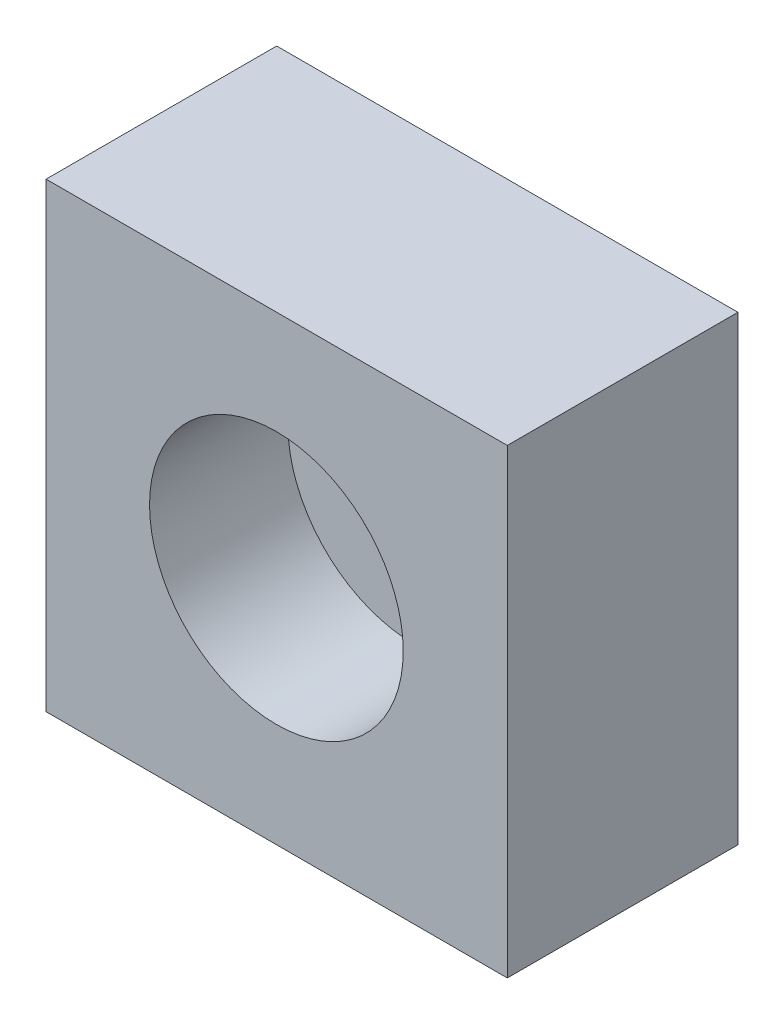
SolidWorks part; units mm, degrees
ref_plane "前视基准面" through (0, 0, 0) normal (0, 0, 1) x (1, 0, 0)
ref_plane "上视基准面" through (0, 0, 0) normal (0, 1, 0) x (1, 0, 0)
ref_plane "右视基准面" through (0, 0, 0) normal (1, 0, 0) x (0, 0, -1)
other "Configuration Table"
sketch "草图1" plane through (0, 0, 0) normal (0, 0, 1) x (1, 0, 0)
  line L1 (0, 0) -> (20, 0)
  line L2 (0, 0) -> (0, 20)
  line L3 (0, 20) -> (20, 20)
  line L4 (20, 0) -> (20, 20)
extrude "BaseBox" add sketch "草图1" along normal blind 10
hole_wizard "Hole_cb_ansi_metric_socket_m6" positions "草图3" profile "草图2" counterbore size "M6" standard "ANSI Metric" end condition through all
sketch "草图3" plane through (0, 0, 10) normal (0, 0, 1) x (1, 0, 0)
  point P0 (9.9865, 10.0143)
sketch "草图2" plane through (9.9865, 10.0143, 10) normal (1, 0, 0) x (0, -1, 0)
  line L0 (0, 0) -> (0, 10)
  line L1 (0, 10) -> (3, 10)
  line L3 (3, 10) -> (3, 6)
  line L4 (3, 6) -> (5.5, 6)
  line L5 (5.5, 6) -> (5.5, 0)
  line L7 (5.5, 0) -> (0, 0)
  line L11 (0, -6.35) -> (0, 107.95) construction
  dimension "通孔孔直径" = 6
  dimension "通孔孔深度" = 10
  dimension "柱形沉头孔直径" = 11
  dimension "柱形沉头孔深度" = 6
